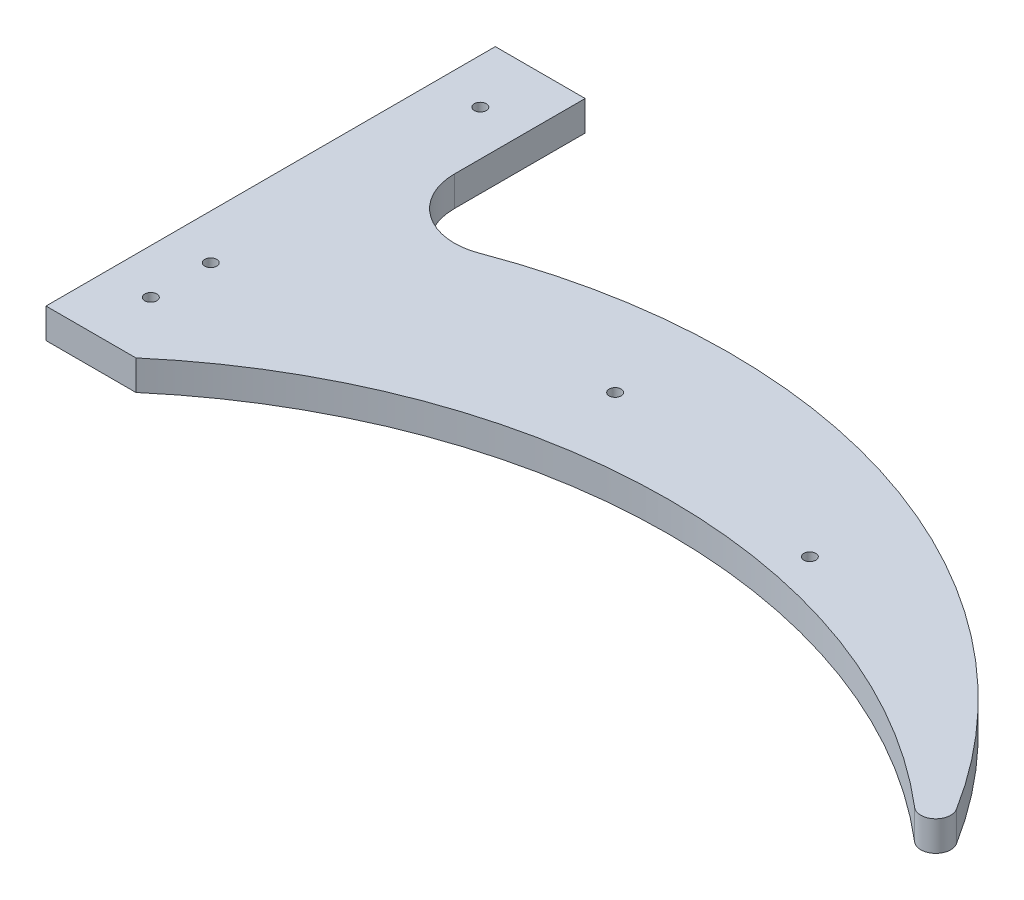
SolidWorks part; units mm, degrees
ref_plane "Front Plane" through (0, 0, 0) normal (0, 0, 1) x (1, 0, 0)
ref_plane "Top Plane" through (0, 0, 0) normal (0, 1, 0) x (1, 0, 0)
ref_plane "Right Plane" through (0, 0, 0) normal (1, 0, 0) x (0, 0, -1)
sketch "Sketch1" plane through (0, 0, 0) normal (0, 1, 0) x (1, 0, 0)
  line L0 (0, 0) -> (130, 0) construction
  line L1 (0, 75) -> (0, 53.1659)
  line L2 (0, 0) -> (-15, 0)
  line L3 (0, 0) -> (0, 75) construction
  line L4 (0, 75) -> (-15, 75)
  line L5 (-15, 0) -> (-15, 75)
  line L6 (-7.5, 0) -> (-7.5, 75) construction
  arc A0 (0, 0) -> (130, 0) centre (65, -75.9934) cw
  arc A1 (13.5374, 43.8125) -> (133.7458, 3.2235) centre (48.9119, -49.7217) cw
  arc A2 (130, 0) -> (133.7458, 3.2235) centre (131.625, 1.8998) ccw
  arc A3 (13.5374, 43.8125) -> (0, 53.1659) centre (10, 53.1659) cw
  circle A4 centre (-7.5, 10) radius 1
  circle A5 centre (-7.5, 20) radius 1
  circle A6 centre (-7.5, 65) radius 1
  circle A7 centre (85, 27.5) radius 1
  circle A8 centre (45, 35) radius 1
  point P13 (0, 37.5)
  dimension "D2" = 100
  dimension "D3" = 100
  dimension "D5" = 2.5
  dimension "D7" = 10
  dimension "D11" = 2
  dimension "D12" = 2
  dimension "D13" = 2
  dimension "D14" = 2
  dimension "D17" = 2
  dimension "D18" = 70
  dimension "D19" = 60
  dimension "D1" = 130
  dimension "D4" = 75
  dimension "D6" = 15
  dimension "D8" = 10
  dimension "D9" = 10
  dimension "D10" = 10
  dimension "D15" = 27.5
  dimension "D16" = 100
extrude "Boss-Extrude1" add sketch "Sketch1" along normal blind 5
